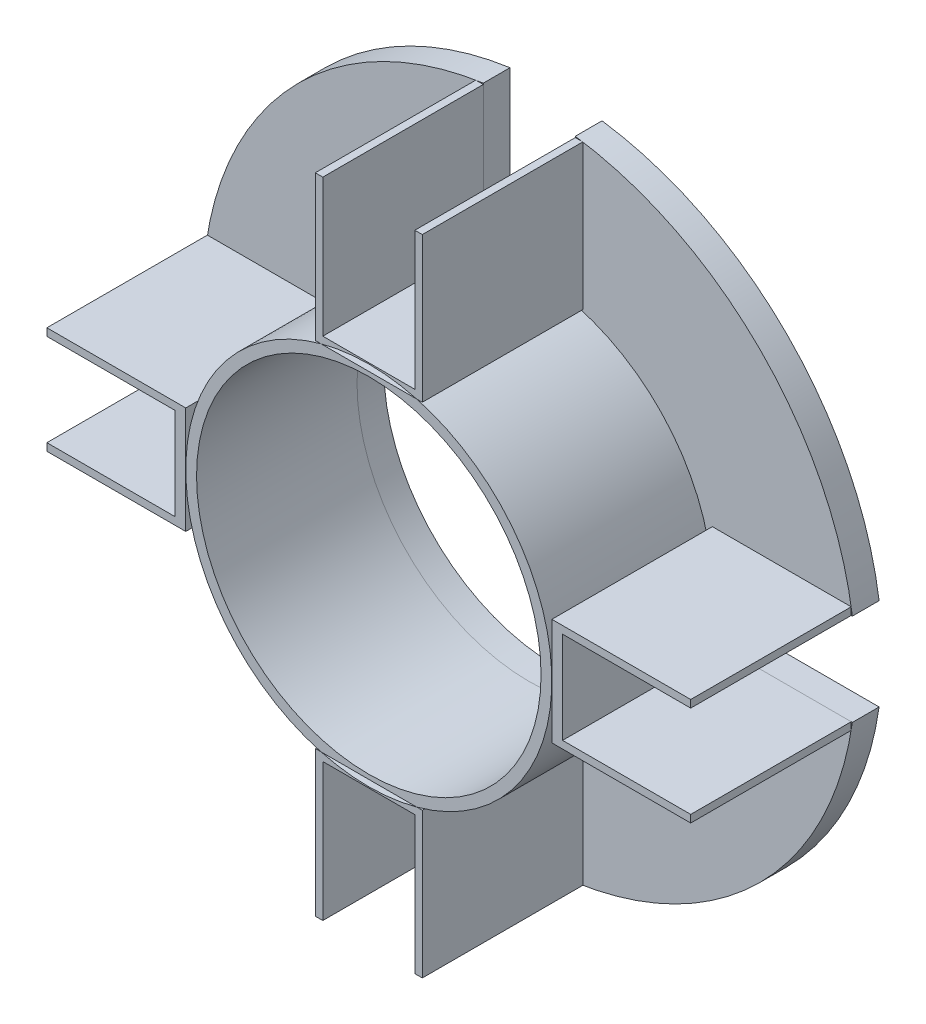
SolidWorks part; units mm, degrees
ref_plane "Front Plane" through (0, 0, 0) normal (0, 0, 1) x (1, 0, 0)
ref_plane "Top Plane" through (0, 0, 0) normal (0, 1, 0) x (1, 0, 0)
ref_plane "Right Plane" through (0, 0, 0) normal (1, 0, 0) x (0, 0, -1)
sketch "Sketch1" plane through (0, 0, 0) normal (0, 0, 1) x (1, 0, 0)
  line L0 (0, 0) -> (30.5, 0)
  line L1 (0, 30.5) -> (0, 0)
  line L2 (-30.5, 0) -> (0, 0)
  line L3 (0, -30.5) -> (0, 0)
  line L4 (-16.1, 0) -> (-30.5, 0)
  line L5 (17.1087, 5) -> (30.0874, 5)
  line L10 (-17.1087, -4.5609) -> (-30.0874, 5) construction
  line L11 (-17.1087, -4.5609) -> (-17.1087, 5)
  line L12 (30.0874, -5) -> (30.0874, 5)
  line L13 (17.1087, -5) -> (30.0874, -5)
  line L14 (17.1087, -5) -> (17.1087, 5)
  line L15 (0, -16.1) -> (0, -30.5)
  line L16 (-5, 30.0874) -> (5, 30.0874)
  line L17 (-5, -16.5126) -> (5, -16.5126)
  line L18 (-5, -16.5126) -> (-5, -30.0874)
  line L19 (-5, -30.0874) -> (5, -30.0874)
  line L20 (5, -16.5126) -> (5, -30.0874)
  line L21 (-5, -16.5126) -> (5, -30.0874) construction
  line L22 (-5, -30.0874) -> (5, -16.5126) construction
  line L23 (5, 16.5126) -> (5, 30.0874)
  line L24 (-5, 16.5126) -> (5, 16.5126)
  line L25 (-5, 16.5126) -> (-5, 30.0874)
  line L26 (-19.9625, 4.3) -> (-29.3874, 4.3)
  line L28 (-19.9625, -4.3) -> (-29.3874, -4.3)
  line L29 (-19.9625, -4.3) -> (-19.9625, 4.3)
  line L30 (-29.3874, -4.3) -> (-30.0874, -4.3)
  line L31 (-30.0874, -4.3) -> (-30.0874, 4.3)
  line L32 (-30.0874, 4.3) -> (-29.3874, 4.3)
  line L34 (-30.0874, -5) -> (-30.0874, 5)
  line L36 (-4.3, -17.2126) -> (-4.3, -29.3874)
  line L38 (4.3, -17.2126) -> (4.3, -29.3874)
  line L39 (-4.3, -17.2126) -> (4.3, -17.2126)
  line L40 (-4.3, -29.3874) -> (-4.3, -30.0874)
  line L41 (-4.3, -30.0874) -> (4.3, -30.0874)
  line L42 (4.3, -30.0874) -> (4.3, -29.3874)
  line L43 (-17.1087, 5) -> (-30.0874, 5)
  line L44 (-4.3, -29.3874) -> (4.3, -29.3874) construction
  line L45 (17.1087, -5) -> (17.1087, 5)
  line L46 (17.1087, -5) -> (30.0874, -5)
  line L47 (30.0874, -5) -> (30.0874, 5)
  line L48 (17.1087, 5) -> (30.0874, 5)
  line L49 (19.9625, -4.3) -> (19.9625, 4.3)
  line L50 (19.9625, 4.3) -> (29.3874, 4.3)
  line L51 (30.0874, 4.3) -> (29.3874, 4.3)
  line L52 (30.0874, -4.3) -> (30.0874, 4.3)
  line L53 (29.3874, -4.3) -> (30.0874, -4.3)
  line L54 (19.9625, -4.3) -> (29.3874, -4.3)
  line L55 (-5, 30.0874) -> (5, 30.0874)
  line L56 (5, 16.5126) -> (5, 30.0874)
  line L57 (-5, 16.5126) -> (5, 16.5126)
  line L58 (-5, 16.5126) -> (-5, 30.0874)
  line L59 (-4.3, 17.2126) -> (4.3, 17.2126)
  line L60 (4.3, 17.2126) -> (4.3, 29.3874)
  line L61 (4.3, 30.0874) -> (4.3, 29.3874)
  line L62 (-4.3, 30.0874) -> (4.3, 30.0874)
  line L63 (-4.3, 29.3874) -> (-4.3, 30.0874)
  line L64 (-4.3, 17.2126) -> (-4.3, 29.3874)
  line L65 (17.1087, -5) -> (30.0874, -5)
  line L66 (-17.1087, -5) -> (-30.0874, -5)
  line L67 (-17.1087, -4.5609) -> (-17.1087, -5)
  circle A0 centre (0, 0) radius 16.1
  circle A1 centre (0, 0) radius 30.5
  circle A2 centre (0, 0) radius 17.1087
  circle A3 centre (0, 0) radius 16.1
  point P9 (-23.3, 0)
  point P19 (0, -23.3)
  dimension "D1" = 10
  dimension "D2" = 0.7
extrude "Boss-Extrude1" add sketch "Sketch1" along normal blind 15
sketch "Sketch2" plane through (0, 0, 0) normal (0, 0, -1) x (-1, 0, 0)
  circle A0 centre (0, 0) radius 30.5
extrude "Boss-Extrude8" add sketch "Sketch2" along normal blind 2.5 separate body
sketch "Sketch3" plane through (17.1087, 0, 0) normal (-1, 0, 0) x (0, 0, 1)
  line L1 (0, 4.3) -> (15, 4.3)
  line L2 (0, 4.3) -> (0, -4.3)
  line L3 (0, -4.3) -> (15, -4.3)
  line L4 (15, 4.3) -> (15, -4.3)
  point P5 (15, -4.3)
  point P9 (0, 5)
  point P10 (0, 4.3)
  point P12 (15, 4.3)
  point P14 (0, 0)
extrude "Cut-Extrude1" cut sketch "Sketch3" against normal up to surface (1.8538 mm away) from offset 1 up to face at (19.9625, 0, 7.5) offset against normal yes
sketch "Sketch4" plane through (-17.1087, 0, 0) normal (1, 0, 0) x (0, 0, -1)
  line L1 (2.5, -4.3) -> (-15, -4.3)
  line L2 (2.5, -4.3) -> (2.5, 4.3)
  line L3 (2.5, 4.3) -> (-15, 4.3)
  line L4 (-15, -4.3) -> (-15, 4.3)
  line L8 (2.5, -30.5) -> (2.5, 30.5) construction
  point P5 (-15, 4.3)
  point P6 (0, 0)
  point P7 (0, -4.3)
  point P8 (0, -4.3)
  point P9 (0, 0)
  point P11 (0, 0)
  point P12 (-15, -4.3)
  point P13 (0, 0)
  point P15 (0, 0)
  point P18 (2.5, -4.3)
extrude "Cut-Extrude2" cut sketch "Sketch4" against normal up to surface (1.8538 mm away) from offset 1 up to face at (-19.9625, 0, 7.5) offset against normal yes
sketch "Sketch5" plane through (0, 0, 0) normal (0, 0, 1) x (1, 0, 0)
  line L1 (-18.1087, 4.3) -> (-36.6006, 4.3)
  line L2 (-18.1087, 4.3) -> (-18.1087, -4.3)
  line L3 (-18.1087, -4.3) -> (-36.6006, -4.3)
  line L4 (-36.6006, 4.3) -> (-36.6006, -4.3)
  line L5 (-4.3, 17.2126) -> (4.3, 17.2126)
  line L6 (-4.3, 17.2126) -> (-4.3, 59.561)
  line L7 (-4.3, 59.561) -> (4.3, 59.561)
  line L8 (4.3, 17.2126) -> (4.3, 59.561)
  line L9 (18.1087, -4.3) -> (55.91, -4.3)
  line L10 (18.1087, -4.3) -> (18.1087, 4.3)
  line L11 (18.1087, 4.3) -> (55.91, 4.3)
  line L12 (55.91, -4.3) -> (55.91, 4.3)
  line L13 (-4.3, -17.2126) -> (4.3, -17.2126)
  line L14 (-4.3, -17.2126) -> (-4.3, -46.2494)
  line L15 (-4.3, -46.2494) -> (4.3, -46.2494)
  line L16 (4.3, -17.2126) -> (4.3, -46.2494)
  circle A0 centre (0, 0) radius 16.1
  point P23 (0, 0)
  point P24 (17.5126, 4.3)
  point P26 (0, 0)
  point P27 (-17.5126, 4.3)
extrude "Cut-Extrude3" cut sketch "Sketch5" against normal up to surface (2.5 mm away) up to face at (-30.5, 0, -2.5)
